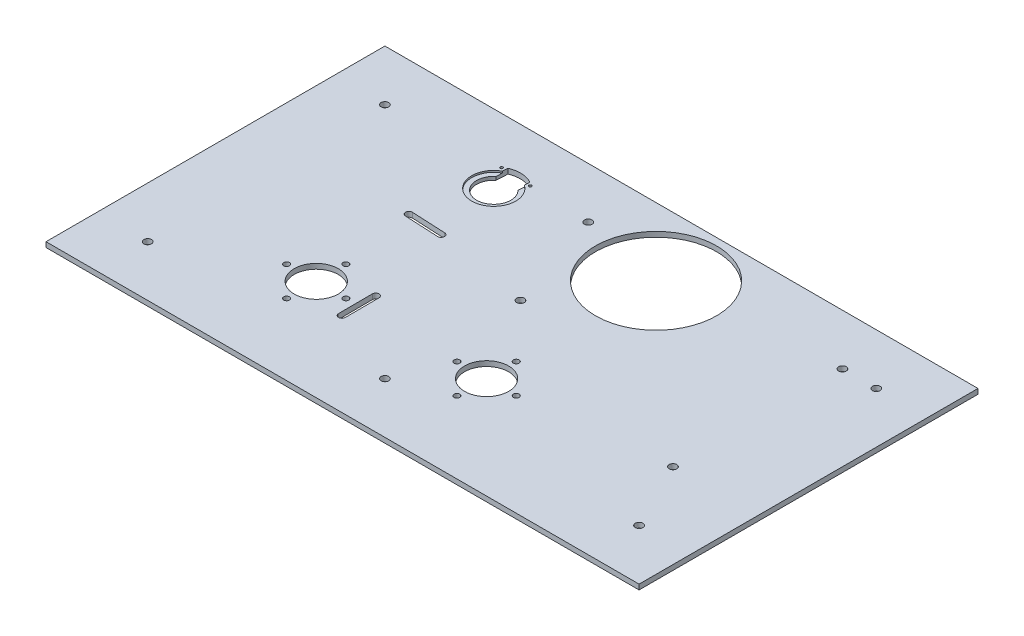
SolidWorks part; units mm, degrees
ref_plane "Front" through (0, 0, 0) normal (0, 0, 1) x (1, 0, 0)
ref_plane "Top" through (0, 0, 0) normal (0, 1, 0) x (1, 0, 0)
ref_plane "Right" through (0, 0, 0) normal (1, 0, 0) x (0, 0, -1)
sketch "Sketch1" plane through (0, 0, 0) normal (0, 1, 0) x (1, 0, 0)
  line L1 (0, 0) -> (200, 0)
  line L2 (0, 0) -> (0, 200)
  line L3 (0, 200) -> (200, 200)
  line L4 (200, 0) -> (200, 200)
  dimension "D1" = 200
  dimension "D2" = 200
extrude "Boss-Extrude1" add sketch "Sketch1" along normal blind 3
sketch "Sketch2" plane through (0, 3, 0) normal (0, 1, 0) x (1, 0, 0)
  line L0 (50.0013, 59.4838) -> (150, 60) construction
  line L1 (150, 160) -> (150, 60) construction
  line L2 (200, 0) -> (200, 200) construction
  line L3 (0, 0) -> (200, 0) construction
  line L4 (75.0526, 49.613) -> (74.9494, 69.6127) construction
  line L5 (73.0526, 49.6027) -> (72.9494, 69.6024)
  line L6 (77.0526, 49.6233) -> (76.9494, 69.6231)
  line L7 (50.0013, 59.4838) -> (54.8734, 159.3651) construction
  line L18 (62.9748, 120.1994) -> (42.9986, 121.1738) construction
  line L19 (62.0297, 166.5049) -> (62.3547, 173.1677)
  line L20 (48.4459, 167.1675) -> (48.7709, 173.8303)
  line L21 (48.4459, 167.1675) -> (62.0297, 166.5049) construction
  line L22 (62.8774, 118.2018) -> (42.9011, 119.1762)
  line L23 (63.0723, 122.197) -> (43.096, 123.1714)
  circle A0 centre (50.0013, 59.4838) radius 13
  circle A1 centre (150, 60) radius 13
  arc A2 (73.0526, 49.6027) -> (77.0526, 49.6233) centre (75.0526, 49.613) ccw
  arc A3 (76.9494, 69.6231) -> (72.9494, 69.6024) centre (74.9494, 69.6127) ccw
  circle A4 centre (150, 160) radius 35.7386
  arc A9 (63.6184, 172.3916) -> (47.4376, 173.1809) centre (54.8842, 159.5868) ccw construction
  arc A10 (48.4459, 167.1675) -> (62.0297, 166.5049) centre (54.8734, 159.3651) ccw
  arc A11 (62.3547, 173.1677) -> (48.7709, 173.8303) centre (54.8842, 159.5868) ccw
  circle A14 centre (46.5919, 172.2639) radius 0.8
  circle A15 centre (64.3708, 171.3967) radius 0.8
  arc A16 (62.8774, 118.2018) -> (63.0723, 122.197) centre (62.9748, 120.1994) ccw
  arc A17 (43.096, 123.1714) -> (42.9011, 119.1762) centre (42.9986, 121.1738) ccw
  point P12 (75.001, 59.6129)
  point P25 (52.9867, 120.6866)
  dimension "D1" = 26
  dimension "D2" = 26
  dimension "D7" = 2
  dimension "D10" = 100
  dimension "D12" = 1.6
  dimension "D13" = 5
  dimension "D14" = 2.1
  dimension "D15" = 71.4773
  dimension "D11" = 15.5
  dimension "D16" = 2
  dimension "D3" = 25
  dimension "D4" = 100
  dimension "D5" = 100
  dimension "D6" = 50
  dimension "D8" = 20
  dimension "D9" = 60
  dimension "D17" = 20
extrude "Cut-Extrude1" cut sketch "Sketch2" against normal through all
hole_wizard "M3 Clearance Hole1" positions "Sketch3" profile "Sketch4" hole size "M3" standard "ISO" end condition through all
sketch "Sketch3" plane through (0, 3, 0) normal (0, 1, 0) x (1, 0, 0)
  circle A0 centre (150, 60) radius 17.5 construction
  circle A1 centre (50.0013, 59.4838) radius 17.5 construction
  point P0 (132.5, 60)
  point P7 (150, 77.5)
  point P9 (150, 42.5)
  point P11 (132.5, 60)
  point P18 (167.5, 60)
  point P23 (50.0013, 76.9838)
  point P25 (50.0013, 41.9838)
  point P27 (67.5013, 59.4838)
  point P29 (32.5013, 59.4838)
  dimension "D1" = 35
  dimension "D2" = 35
sketch "Sketch4" plane through (132.5, 3, -60) normal (1, 0, 0) x (0, 0, 1)
  line L0 (0, 0) -> (0, 3)
  line L1 (0, 3) -> (1.7, 3)
  line L2 (1.7, 3) -> (1.7, 0)
  line L5 (1.7, 0) -> (0, 0)
  line L11 (0, -6.35) -> (0, 107.95) construction
  dimension "Thru Hole Dia." = 3.4
  dimension "Thru Hole Depth" = 3
sketch "Sketch5" plane through (0, 3, 0) normal (0, 1, 0) x (1, 0, 0)
  circle A0 centre (54.8734, 159.3651) radius 13
  dimension "D1" = 26
extrude "Cut-Extrude2" cut sketch "Sketch5" against normal blind 1
sketch "Sketch6" plane through (0, 3, 0) normal (0, 1, 0) x (1, 0, 0)
  line L1 (0, 200) -> (-50, 200)
  line L2 (0, 200) -> (0, 0)
  line L3 (0, 0) -> (-50, 0)
  line L4 (-50, 200) -> (-50, 0)
  line L5 (200, 200) -> (300, 200)
  line L6 (200, 200) -> (200, 0)
  line L7 (200, 0) -> (300, 0)
  line L8 (300, 200) -> (300, 0)
  dimension "D1" = 100
  dimension "D2" = 50
extrude "Boss-Extrude2" add sketch "Sketch6" against normal up to surface (3 mm away) up to face at (150, 0, -75.8)
hole_wizard "M4 Clearance Hole1" positions "Sketch7" profile "Sketch8" hole size "M4" standard "ISO"
sketch "Sketch7" plane through (0, 3, 0) normal (0, 1, 0) x (1, 0, 0)
  line L0 (100, 170) -> (250, 170) construction
  line L1 (250, 170) -> (250, 70) construction
  line L3 (300, 200) -> (-50, 200) construction
  line L4 (300, 0) -> (300, 200) construction
  point P0 (100, 170)
  point P2 (250, 170)
  point P5 (250, 70)
  dimension "D1" = 30
  dimension "D2" = 200
  dimension "D3" = 50
  dimension "D4" = 100
sketch "Sketch8" plane through (100, 3, -170) normal (1, 0, 0) x (0, 0, 1)
  line L0 (0, 0) -> (0, 8.3519)
  line L1 (0, 8.3519) -> (2.25, 7)
  line L2 (2.25, 7) -> (2.25, 0)
  line L5 (2.25, 0) -> (0, 0)
  line L10 (0, 8.3519) -> (-2.25, 7) construction
  line L11 (0, -6.35) -> (0, 107.95) construction
  dimension "Hole Dia." = 4.5
  dimension "Hole Depth" = 7
  dimension "Drill Angle" = 118
hole_wizard "M4 Clearance Hole2" positions "Sketch9" profile "Sketch10" hole size "M4" standard "ISO"
sketch "Sketch9" plane through (0, 3, 0) normal (0, 1, 0) x (1, 0, 0)
  line L1 (-20, 170) -> (270, 170) construction
  line L2 (-20, 170) -> (-20, 30) construction
  line L3 (-20, 30) -> (270, 30) construction
  line L4 (270, 170) -> (270, 30) construction
  line L5 (300, 200) -> (-50, 200) construction
  line L6 (-50, 200) -> (-50, 0) construction
  line L7 (-50, 0) -> (300, 0) construction
  line L8 (300, 0) -> (300, 200) construction
  line L9 (300, 200) -> (-50, 200) construction
  line L10 (120, 110) -> (120, 30) construction
  point P0 (-20, 30)
  point P2 (270, 30)
  point P4 (-20, 170)
  point P6 (270, 170)
  point P156 (120, 110)
  point P167 (120, 30)
  dimension "D1" = 30
  dimension "D2" = 30
  dimension "D3" = 30
  dimension "D4" = 30
  dimension "D5" = 170
  dimension "D6" = 90
  dimension "D7" = 80
sketch "Sketch10" plane through (-20, 3, -30) normal (1, 0, 0) x (0, 0, 1)
  line L0 (0, 0) -> (0, 8.3519)
  line L1 (0, 8.3519) -> (2.25, 7)
  line L2 (2.25, 7) -> (2.25, 0)
  line L5 (2.25, 0) -> (0, 0)
  line L10 (0, 8.3519) -> (-2.25, 7) construction
  line L11 (0, -6.35) -> (0, 107.95) construction
  dimension "Hole Dia." = 4.5
  dimension "Hole Depth" = 7
  dimension "Drill Angle" = 118
